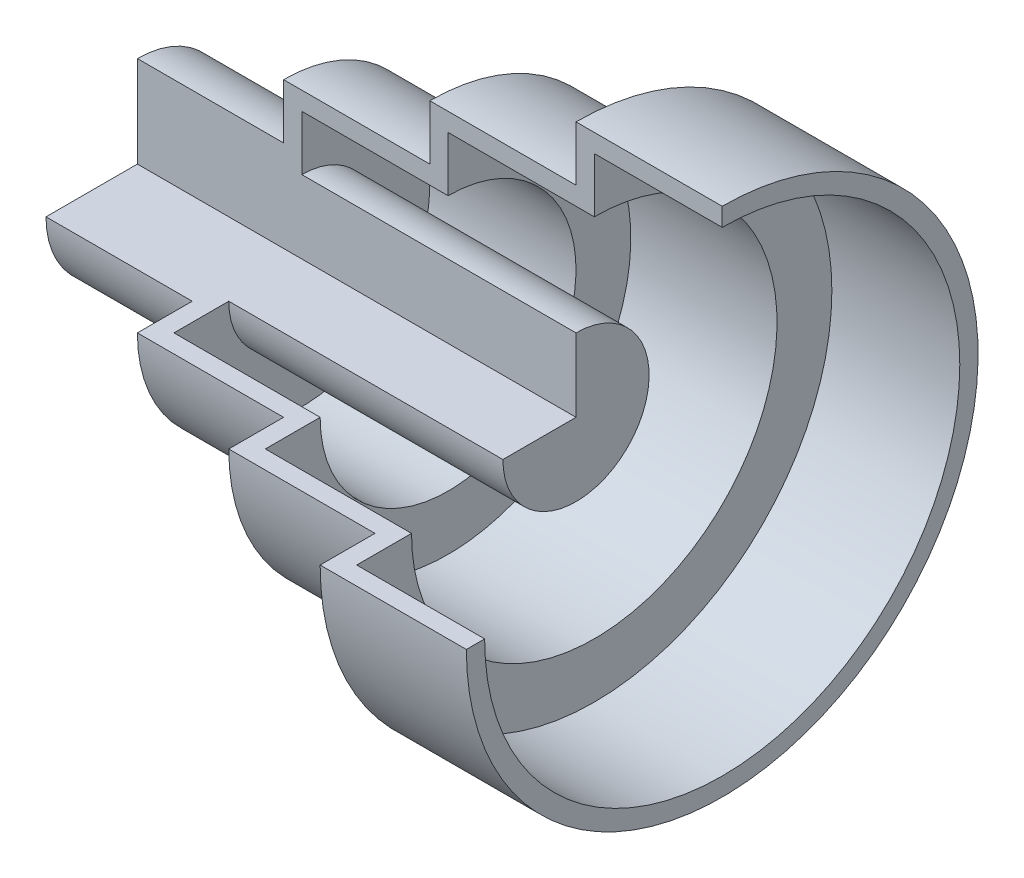
SolidWorks part; units mm, degrees
ref_plane "Front Plane" through (0, 0, 0) normal (0, 0, 1) x (1, 0, 0)
ref_plane "Top Plane" through (0, 0, 0) normal (0, 1, 0) x (1, 0, 0)
ref_plane "Right Plane" through (0, 0, 0) normal (1, 0, 0) x (0, 0, -1)
sketch "Sketch1" plane through (0, 0, 0) normal (0, 0, 1) x (1, 0, 0)
  line L0 (120, 0) -> (0, 0)
  line L1 (0, 0) -> (0, 25)
  line L2 (0, 25) -> (40, 25)
  line L3 (40, 25) -> (40, 40)
  line L4 (80, 40) -> (40, 40)
  line L5 (80, 55) -> (80, 40)
  line L6 (120, 55) -> (80, 55)
  line L7 (120, 55) -> (120, 70)
  line L8 (120, 70) -> (160, 70)
  line L9 (160, 70) -> (160, 65)
  line L10 (160, 65) -> (125, 65)
  line L11 (125, 65) -> (125, 50)
  line L12 (125, 50) -> (85, 50)
  line L13 (85, 35) -> (85, 50)
  line L14 (85, 35) -> (45, 35)
  line L15 (45, 20) -> (45, 35)
  line L16 (120, 20) -> (45, 20)
  line L17 (120, 0) -> (120, 20)
  dimension "D1" = 25
  dimension "120" = 120
  dimension "D2" = 40
  dimension "D3" = 40
  dimension "15" = 15
  dimension "D4" = 15
  dimension "D5" = 40
  dimension "D6" = 15
  dimension "D7" = 40
  dimension "D8" = 15
  dimension "5" = 5
  dimension "35" = 35
  dimension "D9" = 45
revolve "Revolve1" add sketch "Sketch1" angle 270 about L0
